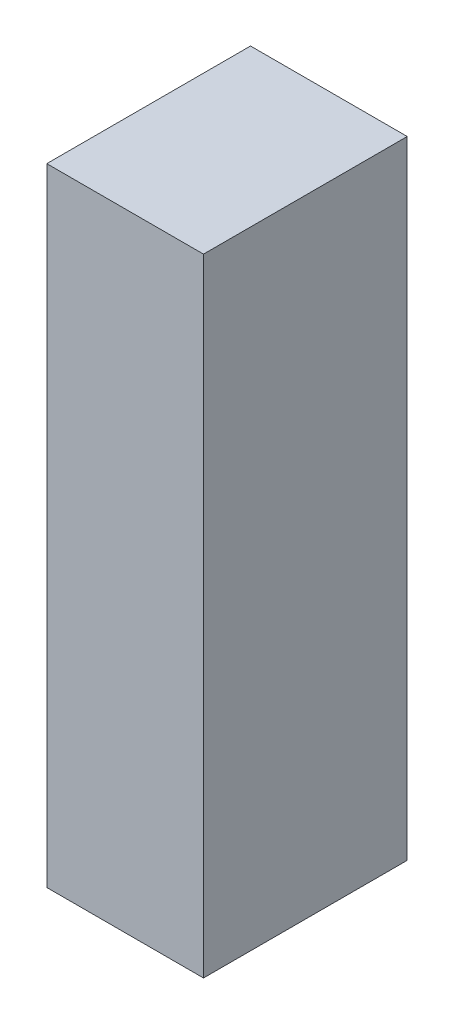
SolidWorks part; units mm, degrees
ref_plane "Front Plane" through (0, 0, 0) normal (0, 0, 1) x (1, 0, 0)
ref_plane "Top Plane" through (0, 0, 0) normal (0, 1, 0) x (1, 0, 0)
ref_plane "Right Plane" through (0, 0, 0) normal (1, 0, 0) x (0, 0, -1)
sketch "Sketch1" plane through (0, 0, 0) normal (0, 1, 0) x (1, 0, 0)
  line L1 (-2.5, 3.25) -> (2.5, 3.25)
  line L2 (-2.5, 3.25) -> (-2.5, -3.25)
  line L3 (-2.5, -3.25) -> (2.5, -3.25)
  line L4 (2.5, 3.25) -> (2.5, -3.25)
  line L5 (-2.5, 3.25) -> (2.5, -3.25) construction
  line L6 (-2.5, -3.25) -> (2.5, 3.25) construction
  point P0 (0, 0)
  dimension "D1" = 5
  dimension "D2" = 6.5
extrude "Boss-Extrude1" add sketch "Sketch1" along normal blind 20
